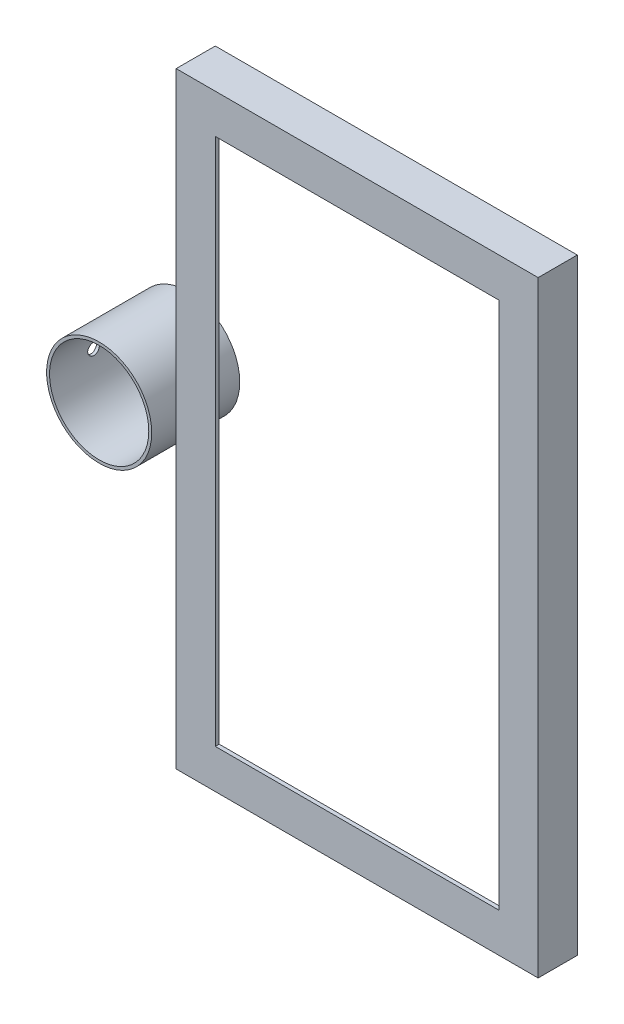
SolidWorks part; units mm, degrees
ref_plane "Front Plane" through (0, 0, 0) normal (0, 0, 1) x (1, 0, 0)
ref_plane "Top Plane" through (0, 0, 0) normal (0, 1, 0) x (1, 0, 0)
ref_plane "Right Plane" through (0, 0, 0) normal (1, 0, 0) x (0, 0, -1)
sketch "Sketch1" plane through (0, 0, 0) normal (0, 0, 1) x (1, 0, 0)
  circle A0 centre (0, 0) radius 26.85
  circle A1 centre (0, 0) radius 25.35
  dimension "D1" = 50.7
  dimension "D2" = 53.7
extrude "Boss-Extrude1" add sketch "Sketch1" along normal blind 45
ref_plane "Plane1" through (-26.85, 0, 0) normal (-1, 0, 0) x (0, 0, 1)
sketch "Sketch2" plane through (-26.85, 0, 0) normal (-1, 0, 0) x (0, 0, 1)
  circle A0 centre (22.5, 0) radius 3
  dimension "D2" = 6
  dimension "D1" = 22.5
extrude "Cut-Extrude2" cut sketch "Sketch2" against normal up to surface (1.5 mm away)
ref_plane "Plane5" through (0, 0, 22.5) normal (0, 0, 1) x (1, 0, 0)
sketch "Sketch9" plane through (0, 0, 22.5) normal (0, 0, 1) x (1, 0, 0)
  line L1 (26.85, 155) -> (211.85, 155)
  line L2 (26.85, 155) -> (26.85, -155)
  line L3 (26.85, -155) -> (211.85, -155)
  line L4 (211.85, 155) -> (211.85, -155)
  line L5 (46.85, 135) -> (191.85, 135)
  line L6 (46.85, 135) -> (46.85, -135)
  line L7 (46.85, -135) -> (191.85, -135)
  line L8 (191.85, 135) -> (191.85, -135)
  circle A0 centre (0, 0) radius 26.85 construction
  point P7 (26.85, 0)
  point P12 (196.5058, -124.5724)
  dimension "D1" = 310
  dimension "D2" = 185
  dimension "D3" = 20
  dimension "D4" = 20
  dimension "D5" = 20
  dimension "D6" = 20
extrude "Boss-Extrude2" add sketch "Sketch9" along normal mid plane 20 separate body
shell "Shell3" thickness 2
